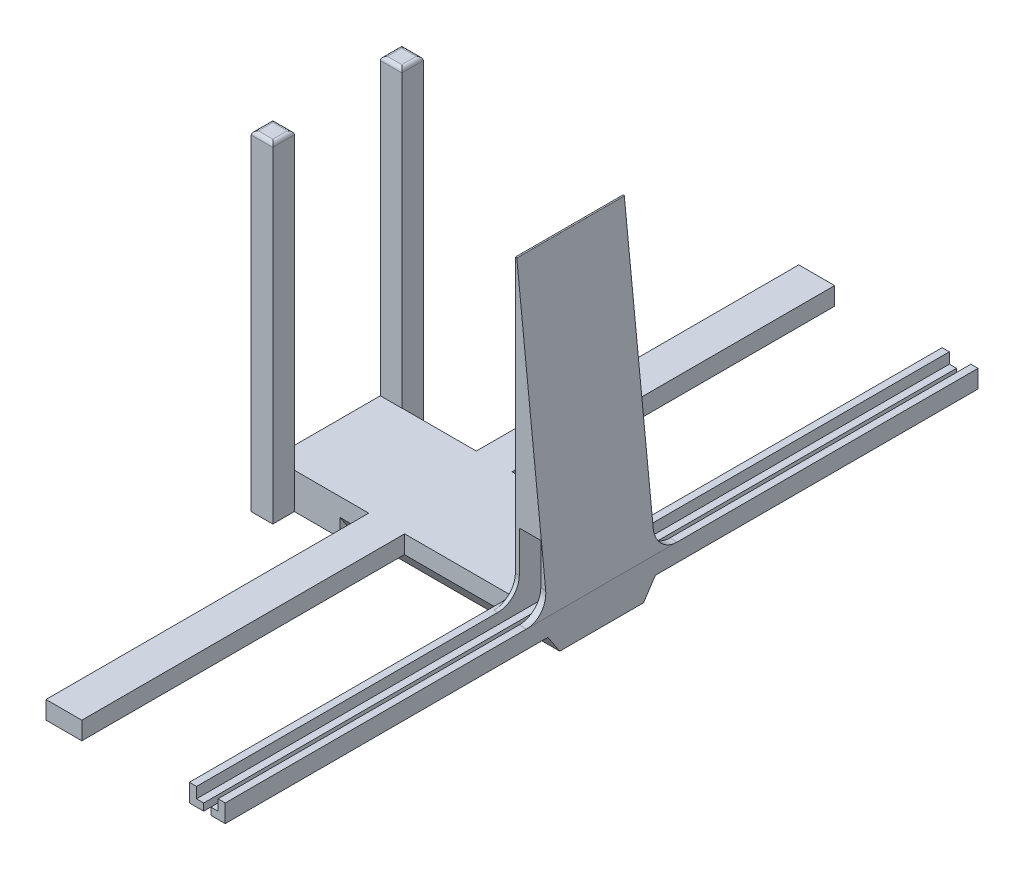
SolidWorks part; units mm, degrees
ref_plane "Front Plane" through (0, 0, 0) normal (0, 0, 1) x (1, 0, 0)
ref_plane "Top Plane" through (0, 0, 0) normal (0, 1, 0) x (1, 0, 0)
ref_plane "Right Plane" through (0, 0, 0) normal (1, 0, 0) x (0, 0, -1)
sketch "Sketch1" plane through (0, -9.4965, 0) normal (0, 1, 0) x (1, 0, 0)
  line L0 (175.5493, -129.0166) -> (125.5493, -129.0166) construction
  line L1 (180.0974, -84.0166) -> (175.0974, -84.0166)
  line L2 (180.0974, -84.0166) -> (180.0974, -189.0166)
  line L3 (180.0974, -189.0166) -> (175.0974, -189.0166)
  line L4 (175.0974, -84.0166) -> (175.0974, -189.0166)
  line L5 (175.5493, -144.0166) -> (125.5493, -144.0166) construction
  dimension "D1" = 60
  dimension "D2" = 60
  dimension "D3" = 5
extrude "Boss-Extrude1" add sketch "Sketch1" along normal blind 5
sketch "Sketch2" plane through (0, -9.4965, 0) normal (0, 0, 1) x (1, 0, 0)
  line L0 (180.0974, 5) -> (175.5493, 48.02)
  line L1 (175.5493, 48.02) -> (175.5493, 5)
  line L2 (180.0974, 5) -> (175.0974, 5) construction
  line L3 (175.5493, 41.5165) -> (175.5493, 56.5165) construction
  line L4 (175.5493, 5) -> (180.0974, 5)
extrude "Boss-Extrude2" add sketch "Sketch2" along normal blind 15 from offset 129
sketch "Sketch3" plane through (0, -9.4965, 0) normal (0, 0, 1) x (1, 0, 0)
  line L1 (175.0974, 5) -> (141.726, 5)
  line L2 (175.0974, 5) -> (175.0974, 0)
  line L3 (175.0974, 0) -> (141.726, 0)
  line L4 (141.726, 5) -> (141.726, 0)
extrude "Boss-Extrude3" add sketch "Sketch3" along normal blind 15 from offset 129
sketch "Sketch4" plane through (0, -9.4965, 0) normal (0, 1, 0) x (1, 0, 0)
  line L0 (175.5493, -144.0166) -> (125.5493, -144.0166) construction
  line L1 (144.726, -147.0166) -> (141.726, -147.0166)
  line L2 (144.726, -147.0166) -> (144.726, -144)
  line L3 (144.726, -144) -> (141.726, -144)
  line L4 (141.726, -147.0166) -> (141.726, -144)
  line L5 (175.5493, -129.0166) -> (125.5493, -129.0166) construction
  line L6 (144.726, -129.0166) -> (141.726, -129.0166)
  line L7 (144.726, -129.0166) -> (144.726, -126.0166)
  line L8 (144.726, -126.0166) -> (141.726, -126.0166)
  line L9 (141.726, -129.0166) -> (141.726, -126.0166)
  dimension "D1" = 3
  dimension "D2" = 3
  dimension "D3" = 3
  dimension "D4" = 3
extrude "Boss-Extrude4" add sketch "Sketch4" along normal blind 46
sketch "Sketch5" plane through (0, 0, 126.0166) normal (0, 0, -1) x (-1, 0, 0)
  circle A0 centre (-143.2664, 42.1424) radius 0.7
fillet "Fillet1" radius 0.5 8 edges at (143.226, 36.5035, 129.0166) (141.726, 36.5035, 127.5166) (143.226, 36.5035, 126.0166) (144.726, 36.5035, 127.5166) (143.226, 36.5035, 147.0166) (141.726, 36.5035, 145.5083) (143.226, 36.5035, 144) (144.726, 36.5035, 145.5083)
fillet "Fillet2" radius 0.1 1 edges at (175.5493, 38.5235, 136.5)
sketch "Sketch6" plane through (177.6366, 18.7798, 0) normal (0.9945, 0.1051, 0) x (0, 0, -1)
  line L0 (-144, -23.4061) -> (-144, 17.9566) construction
  line L1 (-129, -23.4061) -> (-129, 17.9566) construction
  circle A0 centre (-141.5, 22.489) radius 0.7
  circle A1 centre (-131.5, 22.489) radius 0.7
  dimension "D1" = 2.5
  dimension "D2" = 2.5
ref_plane "Plane1" through (180.0974, -4.4965, 144) normal (1, 0, 0) x (0, 0, -1)
fillet "Fillet3" radius 3 2 edges at (177.8233, -4.4965, 129) (177.8233, -4.4965, 144)
pattern_linear "LPattern2" count 2 spacing 20 along (-1, 0, 0) of "Boss-Extrude1"
sketch "Sketch7" plane through (180.0974, 0, 0) normal (1, 0, 0) x (0, 0, -1)
  line L0 (-189.0166, -9.4965) -> (-84.0166, -9.4965)
  line L1 (-84.0166, -9.4965) -> (-84.0166, -6.9965)
  line L2 (-84.0166, -4.4965) -> (-84.0166, -9.4965) construction
  line L3 (-84.0166, -6.9965) -> (-129.0166, -6.9965)
  line L4 (-129.0166, -6.9965) -> (-130.6749, -9.4965)
  line L5 (-130.6749, -9.4965) -> (-142.3583, -9.4965)
  line L6 (-142.3583, -9.4965) -> (-144.0166, -6.9965)
  line L7 (-144.0166, -6.9965) -> (-189.0166, -6.9965)
  line L8 (-189.0166, -4.4965) -> (-189.0166, -9.4965) construction
  line L9 (-189.0166, -6.9965) -> (-189.0166, -9.4965)
  line M7 (-189.0166, -9.4965) -> (-84.0166, -9.4965)
  line M8 (-84.0166, -9.4965) -> (-84.0166, -4.4965)
  line M12 (-189.0166, -4.4965) -> (-189.0166, -9.4965)
  dimension "D1" = 2.5
  dimension "D2" = 45
  dimension "D3" = 45
  dimension "D4" = 2.5
  dimension "D5" = 3
  dimension "D6" = 3
extrude "Cut-Extrude3" cut sketch "Sketch7" against normal blind 29 contours L3 L4 L0 M8 | L6 L7 M12 M7
sketch "Sketch10" plane through (0, -4.4965, 0) normal (0, 1, 0) x (1, 0, 0)
  line L1 (240.0974, -85.051) -> (151.0974, -85.051)
  line L2 (240.0974, -85.051) -> (240.0974, -92.051)
  line L3 (240.0974, -92.051) -> (151.0974, -92.051)
  line L4 (151.0974, -85.051) -> (151.0974, -92.051)
sketch "Sketch11" plane through (0, 0, 84.0166) normal (0, 0, -1) x (-1, 0, 0)
  line L0 (-178.0974, -6.9965) -> (-178.0974, -5.9965)
  line L1 (-175.0974, -6.9965) -> (-180.0974, -6.9965) construction
  line L2 (-178.0974, -5.9965) -> (-179.0974, -5.9965)
  line L3 (-179.0974, -5.9965) -> (-179.0974, 4.2082)
  line L4 (-179.0974, 4.2082) -> (-176.0974, 4.2082)
  line L5 (-176.0974, 4.2082) -> (-176.0974, -5.9965)
  line L6 (-176.0974, -5.9965) -> (-177.0974, -5.9965)
  line L7 (-177.0974, -5.9965) -> (-177.0974, -6.9965)
  line L8 (-177.0974, -6.9965) -> (-178.0974, -6.9965)
  line L9 (-180.0974, -4.4965) -> (-180.0974, -6.9965) construction
  line L10 (-175.0974, -4.4965) -> (-175.0974, -6.9965) construction
  dimension "D1" = 2
  dimension "D2" = 2
  dimension "D3" = 1
  dimension "D4" = 1
  dimension "D5" = 1
  dimension "D6" = 1
extrude "Cut-Extrude4" cut sketch "Sketch11" against normal blind 106
